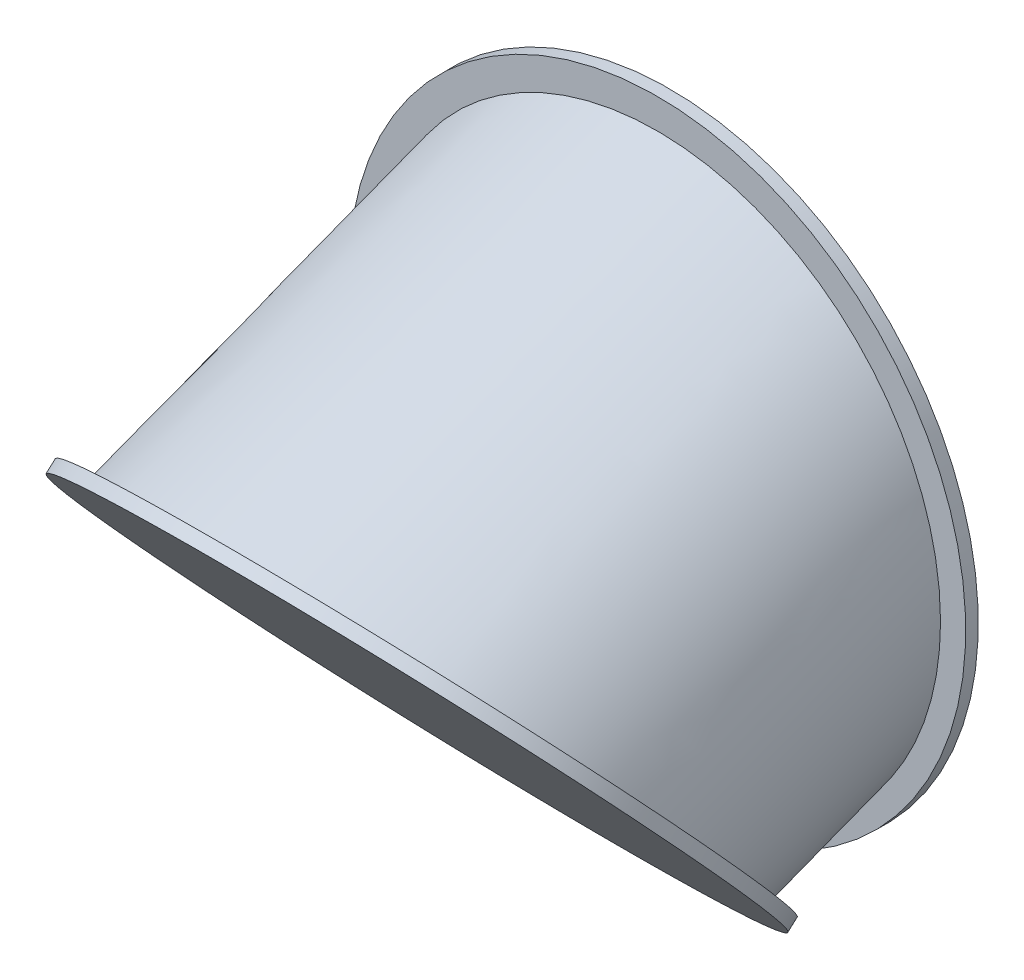
SolidWorks part; units mm, degrees
ref_plane "Front Plane" through (0, 0, 0) normal (0, 0, 1) x (1, 0, 0)
ref_plane "Top Plane" through (0, 0, 0) normal (0, 1, 0) x (1, 0, 0)
ref_plane "Right Plane" through (0, 0, 0) normal (1, 0, 0) x (0, 0, -1)
sketch "Sketch3" plane through (0, 0, 0) normal (1, 0, 0) x (0, 0, -1)
  line L0 (-38.8581, 0) -> (32.5956, 0) construction
  line L1 (0, 0) -> (-23.3395, -8.9592)
  dimension "D1" = 21
  dimension "D2" = 25
sketch "Sketch1" plane through (0, 0, 0) normal (0, 0, 1) x (1, 0, 0)
  line L0 (0, 33.9315) -> (0, -46.4875) construction
  line L1 (-26.1917, -15) -> (26.495, -15) construction
  circle A0 centre (0, 0) radius 11.25
  dimension "D1" = 22.5
  dimension "D2" = 15
sweep "Sweep1" add profiles "Sketch1" path "Sketch3"
ref_plane "Plane3" through (0, -6.716, 7.4589) normal (0, -0.6691, 0.7431) x (1, 0, 0)
other "SurfaceCut3"
sketch "Sketch9" plane through (0, 0, 0) normal (0, 0, -1) x (-1, 0, 0)
  circle A0 centre (0, 0) radius 11.25 construction
  circle A1 centre (0, 0) radius 11.25 construction
  circle A2 centre (0, 0) radius 12.25
  dimension "D1" = 1
sketch "Sketch11" plane through (0, -6.716, 7.4589) normal (0, -0.6691, 0.7431) x (1, 0, 0)
  circle A0 centre (0, 3.8528) radius 12.25
  circle A1 centre (0, 3.8528) radius 11.25
  circle A2 centre (0, 3.8528) radius 11.25 construction
  dimension "D2" = 1
  dimension "D1" = 0
extrude "Boss-Extrude2" add sketch "Sketch11" against normal blind 0.5 contours A0
extrude "Boss-Extrude3" add sketch "Sketch9" against normal blind 0.5 contours A2
